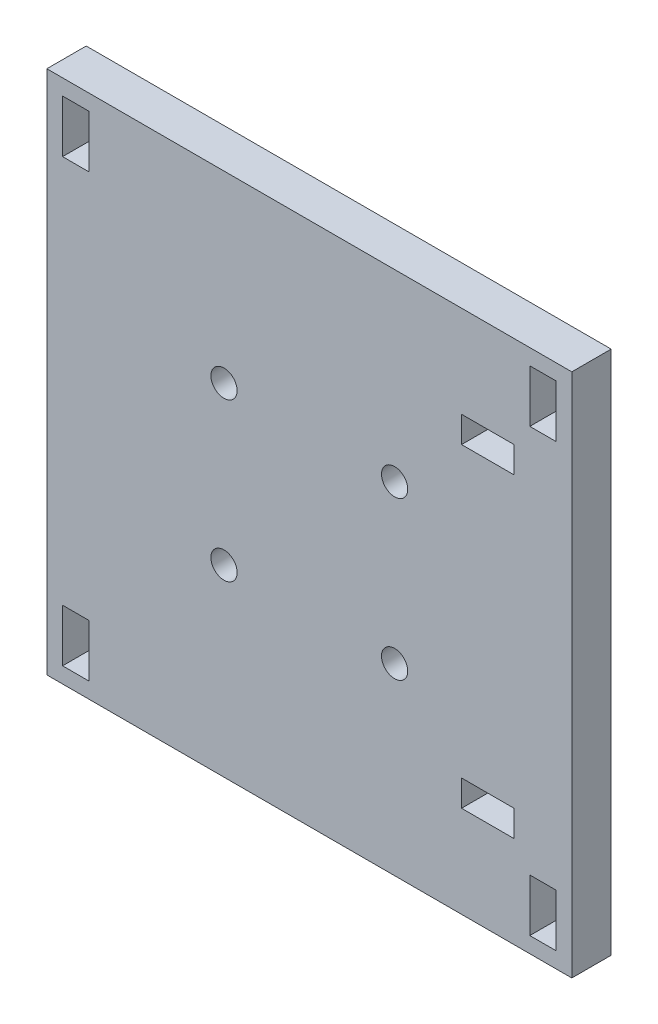
SolidWorks part; units mm, degrees
material "ABS"
ref_plane "Alzado" through (0, 0, 0) normal (0, 0, 1) x (1, 0, 0)
ref_plane "Planta" through (0, 0, 0) normal (0, 1, 0) x (1, 0, 0)
ref_plane "Vista lateral" through (0, 0, 0) normal (1, 0, 0) x (0, 0, -1)
sketch "Sketch1" plane through (0, 0, 0) normal (0, 0, 1) x (1, 0, 0)
  line L0 (0, -1000) -> (0, 49000) construction
  line L5 (-1000, 0) -> (49000, 0) construction
  line L7 (-20, -20) -> (20, -20)
  line L8 (-20, -20) -> (-20, 20)
  line L9 (-20, 20) -> (20, 20)
  line L10 (20, -20) -> (20, 20)
  line L11 (-20, -20) -> (20, 20) construction
  line L12 (-20, 20) -> (20, -20) construction
  circle A0 centre (6.5, -6) radius 1
  circle A1 centre (-6.5, -6) radius 1
  circle A2 centre (6.5, 6) radius 1
  circle A3 centre (-6.5, 6) radius 1
  point P14 (0, 0)
  dimension "D3" = 2
  dimension "D1" = 6
  dimension "D2" = 6.5
  dimension "D4" = 40
  dimension "D5" = 40
extrude "Boss-Extrude1" add sketch "Sketch1" along normal blind 3
sketch "Sketch2" plane through (0, 0, 3) normal (0, 0, 1) x (1, 0, 0)
  line L0 (0, 20) -> (0, -20) construction
  line L1 (20, 20) -> (-20, 20) construction
  line L2 (-20, -20) -> (20, -20) construction
  line L3 (-20, 0) -> (20, 0) construction
  line L4 (-20, 20) -> (-20, -20) construction
  line L5 (20, -20) -> (20, 20) construction
  line L6 (18.8, 14.8) -> (16.8, 14.8)
  line L7 (-18.8, 18.8) -> (-16.8, 18.8)
  line L8 (-18.8, 18.8) -> (-18.8, 14.8)
  line L9 (-18.8, 14.8) -> (-16.8, 14.8)
  line L10 (-16.8, 18.8) -> (-16.8, 14.8)
  line L23 (11.6, 13) -> (15.6, 13)
  line L24 (11.6, 13) -> (11.6, 11)
  line L25 (11.6, 11) -> (15.6, 11)
  line L26 (15.6, 13) -> (15.6, 11)
  line L31 (18.8, 18.8) -> (18.8, 14.8)
  line L32 (18.8, 18.8) -> (16.8, 18.8)
  line L33 (16.8, 18.8) -> (16.8, 14.8)
  line L34 (16.8, -18.8) -> (16.8, -14.8)
  line L35 (18.8, -18.8) -> (16.8, -18.8)
  line L36 (18.8, -18.8) -> (18.8, -14.8)
  line L37 (18.8, -14.8) -> (16.8, -14.8)
  line L38 (-18.8, -14.8) -> (-16.8, -14.8)
  line L39 (-18.8, -18.8) -> (-18.8, -14.8)
  line L40 (-18.8, -18.8) -> (-16.8, -18.8)
  line L41 (-16.8, -18.8) -> (-16.8, -14.8)
  line L42 (15.6, -13) -> (15.6, -11)
  line L43 (11.6, -11) -> (15.6, -11)
  line L44 (11.6, -13) -> (11.6, -11)
  line L45 (11.6, -13) -> (15.6, -13)
  point P36 (15.6, 12)
  dimension "D1" = 4
  dimension "D2" = 2
  dimension "D3" = 1.2
  dimension "D4" = 1.2
  dimension "D5" = 2
  dimension "D6" = 4
  dimension "D7" = 1.2
  dimension "D8" = 1.8
extrude "Cut-Extrude1" cut sketch "Sketch2" against normal through all
